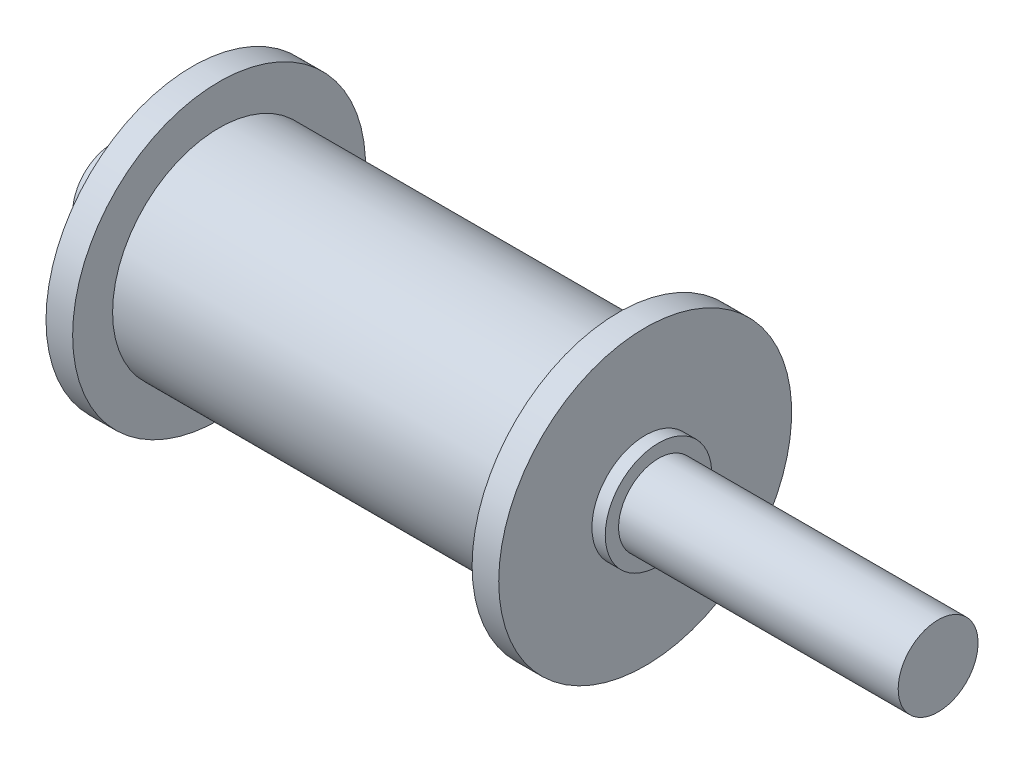
SolidWorks part; units mm, degrees
material "1060 合金"
ref_plane "前视基准面" through (0, 0, 0) normal (0, 0, 1) x (1, 0, 0)
ref_plane "上视基准面" through (0, 0, 0) normal (0, 1, 0) x (1, 0, 0)
ref_plane "右视基准面" through (0, 0, 0) normal (1, 0, 0) x (0, 0, -1)
sketch "草图2" plane through (0, 0, 0) normal (0, 0, 1) x (1, 0, 0)
  line L0 (32, 11) -> (34, 11)
  line L1 (-6, 0) -> (56, 0)
  line L2 (0, 4) -> (0, 11)
  line L3 (0, 11) -> (2, 11)
  line L4 (34, 4) -> (34, 11)
  line L5 (-1, 3) -> (-6, 3)
  line L6 (2, 11) -> (2, 8)
  line L7 (2, 8) -> (32, 8)
  line L8 (32, 11) -> (32, 8)
  line L9 (-6, 3) -> (-6, 0)
  line L10 (35, 3) -> (56, 3)
  line L11 (56, 3) -> (56, 0)
  line L12 (-1, 3) -> (-1, 4)
  line L13 (-1, 4) -> (0, 4)
  line L14 (34, 4) -> (35, 4)
  line L15 (35, 4) -> (35, 3)
  circle A0 centre (4.5, 10.5) radius 2.5 construction
  dimension "D3" = 5
  dimension "D1" = 2
  dimension "D2" = 2
  dimension "D4" = 3
  dimension "D5" = 8
  dimension "D6" = 30
  dimension "D7" = 3
  dimension "D8" = 3
  dimension "D9" = 5
  dimension "D10" = 1
  dimension "D11" = 1
  dimension "D12" = 1
  dimension "D13" = 1
  dimension "D14" = 21
revolve "旋转1" add sketch "草图2" angle 360 about L1
sketch "草图5" plane through (0, 0, 0) normal (0, 0, 1) x (1, 0, 0)
  line L0 (32, 8) -> (2, 8) construction
  line L1 (32, 8) -> (2, 8) construction
  line L2 (2, -11) -> (2, 11) construction
  line L3 (0, 0) -> (37.0214, 0) construction
  circle A0 centre (4, 10) radius 2
  dimension "D1" = 4
revolve "旋转2" [suppressed] add sketch "草图5" angle 360 about L3
pattern_linear "阵列(线性)2" [suppressed] count 8 spacing 4
